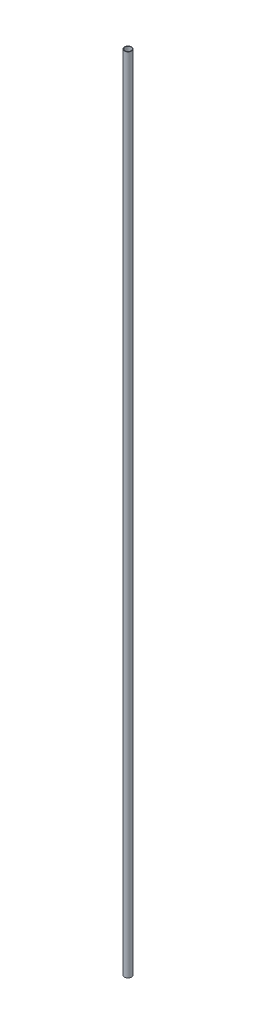
SolidWorks part; units mm, degrees
ref_plane "Front Plane" through (0, 0, 0) normal (0, 0, 1) x (1, 0, 0)
ref_plane "Top Plane" through (0, 0, 0) normal (0, 1, 0) x (1, 0, 0)
ref_plane "Right Plane" through (0, 0, 0) normal (1, 0, 0) x (0, 0, -1)
sketch "Sketch1" plane through (0, 0, 0) normal (0, 1, 0) x (1, 0, 0)
  circle A0 centre (0, 0) radius 4
  circle A1 centre (0, 0) radius 3.5
  dimension "D1" = 8
  dimension "D2" = 7
extrude "Boss-Extrude1" add sketch "Sketch1" along normal blind 891.83
